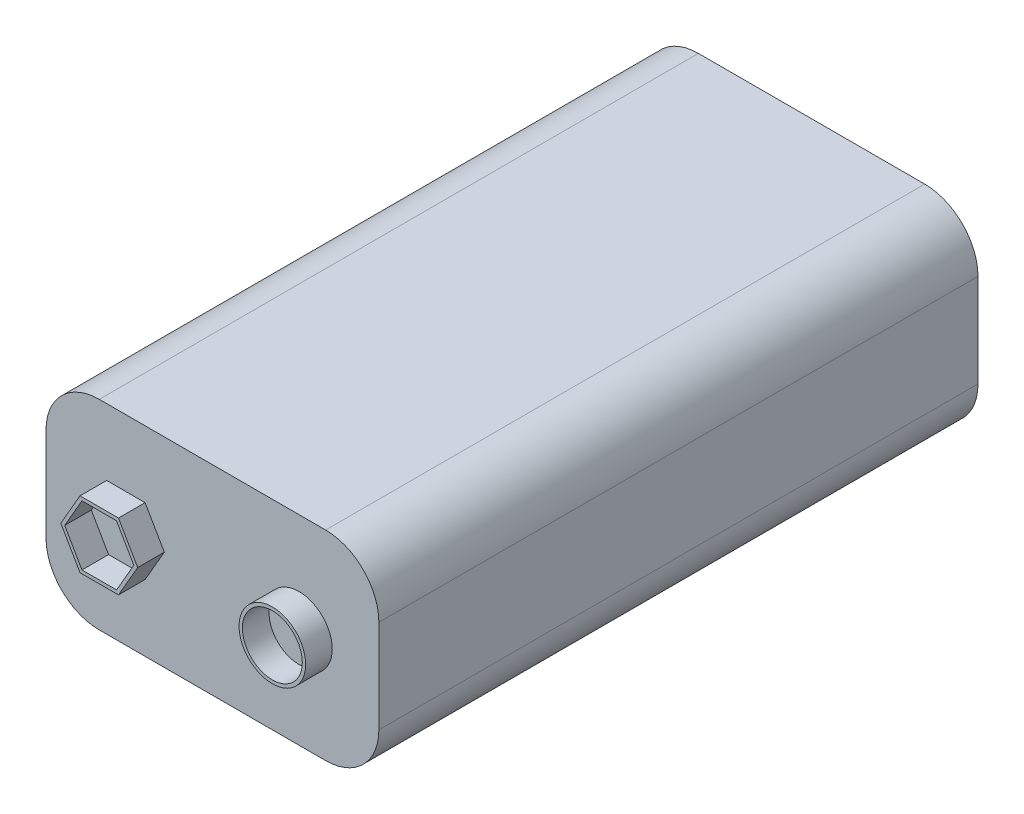
SolidWorks part; units mm, degrees
ref_plane "Front Plane" through (0, 0, 0) normal (0, 0, 1) x (1, 0, 0)
ref_plane "Top Plane" through (0, 0, 0) normal (0, 1, 0) x (1, 0, 0)
ref_plane "Right Plane" through (0, 0, 0) normal (1, 0, 0) x (0, 0, -1)
sketch "Sketch1" plane through (0, 0, 0) normal (0, 0, 1) x (1, 0, 0)
  line L1 (4, 0) -> (21, 0)
  line L2 (0, 4) -> (0, 11)
  line L3 (4, 15) -> (21, 15)
  line L4 (25, 4) -> (25, 11)
  arc A0 (21, 15) -> (25, 11) centre (21, 11) cw
  arc A1 (25, 4) -> (21, 0) centre (21, 4) cw
  arc A2 (4, 0) -> (0, 4) centre (4, 4) cw
  arc A3 (0, 11) -> (4, 15) centre (4, 11) cw
  point P9 (25, 0)
  point P12 (0, 0)
  point P15 (0, 15)
  dimension "D3" = 4
  dimension "D1" = 15
  dimension "D2" = 25
extrude "Boss-Extrude1" add sketch "Sketch1" along normal blind 45
sketch "Sketch2" plane through (0, 0, 45) normal (0, 0, 1) x (1, 0, 0)
  line L0 (25, 4) -> (25, 11) construction
  line L1 (8.8868, 7.5) -> (7.4434, 10)
  line L2 (7.4434, 10) -> (4.5566, 10)
  line L3 (4.5566, 10) -> (3.1132, 7.5)
  line L4 (3.1132, 7.5) -> (4.5566, 5)
  line L5 (4.5566, 5) -> (7.4434, 5)
  line L6 (7.4434, 5) -> (8.8868, 7.5)
  line L8 (21, 15) -> (4, 15) construction
  line L9 (0, 11) -> (0, 4) construction
  line L10 (8.5981, 7.5) -> (7.299, 9.75)
  line L11 (7.299, 9.75) -> (4.701, 9.75)
  line L12 (4.701, 9.75) -> (3.4019, 7.5)
  line L13 (3.4019, 7.5) -> (4.701, 5.25)
  line L14 (4.701, 5.25) -> (7.299, 5.25)
  line L15 (7.299, 5.25) -> (8.5981, 7.5)
  circle A0 centre (19, 7.5) radius 2.5
  circle A1 centre (6, 7.5) radius 2.5 construction
  circle A2 centre (19, 7.5) radius 2.25
  circle A3 centre (6, 7.5) radius 2.25 construction
  dimension "D1" = 5
  dimension "D5" = 5
  dimension "D6" = 4.5
  dimension "D7" = 4.5
  dimension "D2" = 6
  dimension "D3" = 7.5
  dimension "D4" = 6
extrude "Boss-Extrude2" add sketch "Sketch2" along normal blind 2
